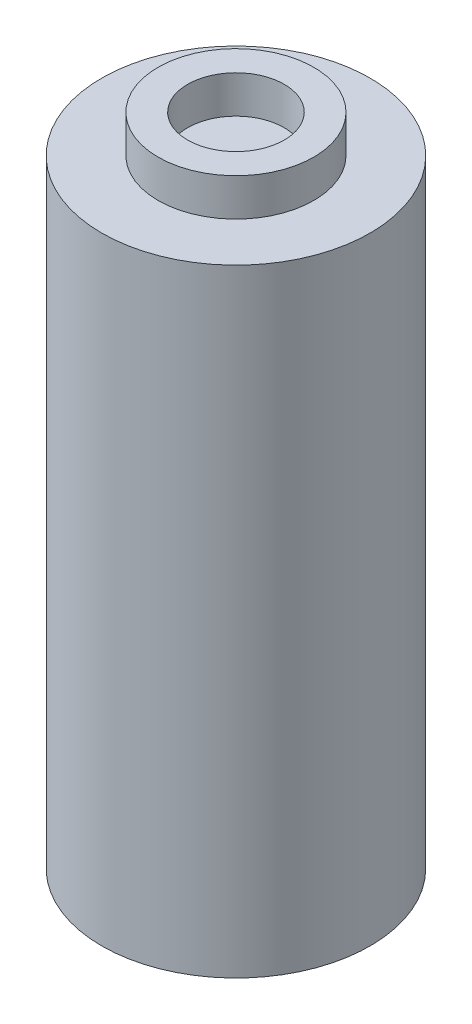
SolidWorks part; units mm, degrees
ref_plane "Plan de face" through (0, 0, 0) normal (0, 0, 1) x (1, 0, 0)
ref_plane "Plan de dessus" through (0, 0, 0) normal (0, 1, 0) x (1, 0, 0)
ref_plane "Plan de droite" through (0, 0, 0) normal (1, 0, 0) x (0, 0, -1)
sketch "Esquisse1" plane through (0, 0, 0) normal (0, 1, 0) x (1, 0, 0)
  circle A0 centre (0, 0) radius 5
extrude "Boss.-Extru.1" add sketch "Esquisse1" along normal blind 23
sketch "Esquisse2" plane through (0, 23, 0) normal (0, 1, 0) x (1, 0, 0)
  circle A0 centre (0, 0) radius 2.9
  circle A1 centre (0, 0) radius 1.8
extrude "Boss.-Extru.2" add sketch "Esquisse2" along normal blind 1.4
